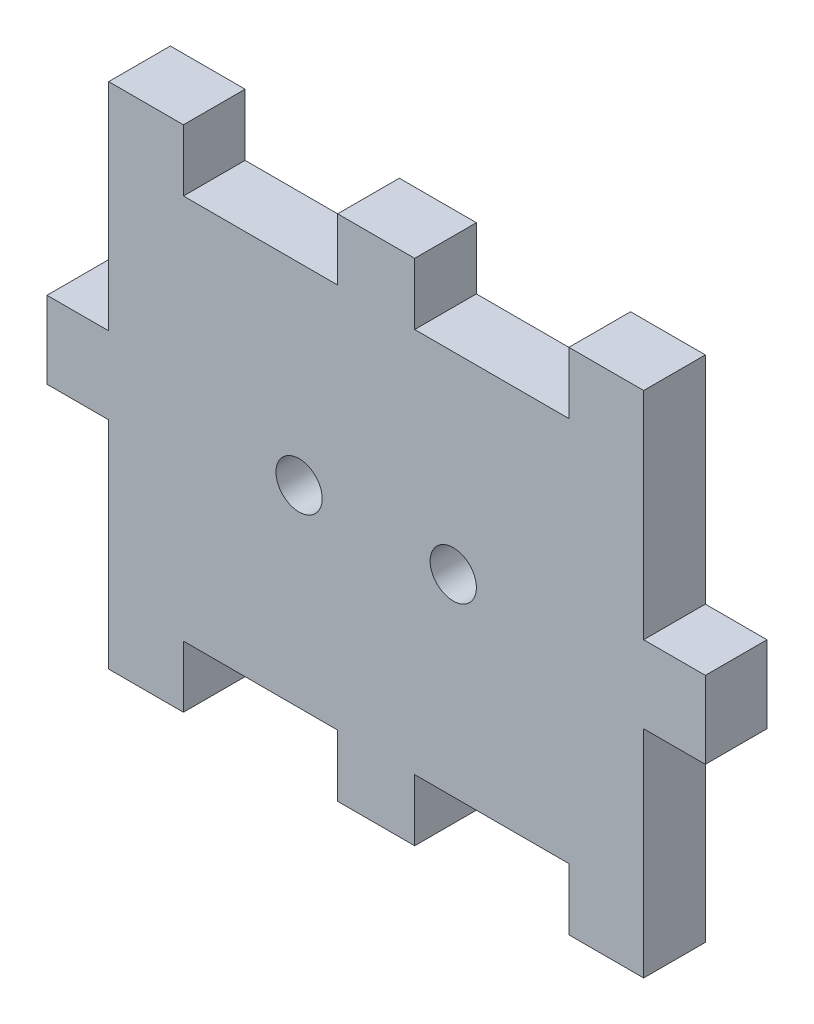
SolidWorks part; units mm, degrees
ref_plane "Спереди" through (0, 0, 0) normal (0, 0, 1) x (1, 0, 0)
ref_plane "Сверху" through (0, 0, 0) normal (0, 1, 0) x (1, 0, 0)
ref_plane "Справа" through (0, 0, 0) normal (1, 0, 0) x (0, 0, -1)
other "Configuration Table"
sketch "Эскиз1" plane through (0, 0, 0) normal (0, 0, 1) x (1, 0, 0)
  line L0 (-4, -4) -> (-4, 29)
  line L1 (0, 0) -> (34.7, 0) construction
  line L2 (0, 0) -> (0, 25) construction
  line L3 (0, 25) -> (34.7, 25) construction
  line L4 (34.7, 0) -> (34.7, 25) construction
  line L7 (-4, 29) -> (38.7, 29)
  line L8 (38.7, -4) -> (38.7, 29)
  line L9 (-4, -4) -> (38.7, -4)
  dimension "D3" = 4
  dimension "D1" = 25
  dimension "D2" = 34.7
extrude "Бобышка-Вытянуть1" add sketch "Эскиз1" along normal blind 4
sketch "Эскиз2" plane through (0, 0, 4) normal (0, 0, 1) x (1, 0, 0)
  line L0 (38.7, 29) -> (-4, 29) construction
  line L1 (4.85, 29) -> (14.85, 29)
  line L2 (4.85, 29) -> (4.85, 25)
  line L3 (4.85, 25) -> (14.85, 25)
  line L4 (14.85, 29) -> (14.85, 25)
  line L5 (17.35, 29) -> (17.35, -4) construction
  line L6 (-4, -4) -> (38.7, -4) construction
  line L7 (19.85, 29) -> (19.85, 25)
  line L8 (29.85, 25) -> (19.85, 25)
  line L9 (29.85, 29) -> (29.85, 25)
  line L10 (29.85, 29) -> (19.85, 29)
  line L11 (-4, 12.5) -> (38.7, 12.5) construction
  line L12 (-4, 29) -> (-4, -4) construction
  line L13 (38.7, -4) -> (38.7, 29) construction
  line L14 (-4, -4) -> (0, -4)
  line L15 (-4, 15) -> (0, 15)
  line L16 (-4, 15) -> (-4, 29)
  line L17 (-4, 29) -> (0, 29)
  line L18 (0, 15) -> (0, 29)
  line L19 (0, 10) -> (0, -4)
  line L20 (-4, 10) -> (0, 10)
  line L21 (-4, 10) -> (-4, -4)
  line L22 (29.85, -4) -> (19.85, -4)
  line L23 (29.85, -4) -> (29.85, 0)
  line L24 (29.85, 0) -> (19.85, 0)
  line L25 (19.85, -4) -> (19.85, 0)
  line L26 (14.85, -4) -> (14.85, 0)
  line L27 (4.85, 0) -> (14.85, 0)
  line L28 (4.85, -4) -> (4.85, 0)
  line L29 (4.85, -4) -> (14.85, -4)
  line L30 (38.7, 10) -> (38.7, -4)
  line L31 (38.7, 10) -> (34.7, 10)
  line L32 (34.7, 10) -> (34.7, -4)
  line L33 (34.7, 15) -> (34.7, 29)
  line L34 (38.7, 29) -> (34.7, 29)
  line L35 (38.7, 15) -> (38.7, 29)
  line L36 (38.7, 15) -> (34.7, 15)
  line L37 (38.7, -4) -> (34.7, -4)
  circle A0 centre (12.35, 12.5) radius 1.5
  circle A1 centre (22.35, 12.5) radius 1.5
  point P48 (12.35, 12.5)
  dimension "D7" = 3
  dimension "D1" = 4
  dimension "D2" = 10
  dimension "D3" = 5
  dimension "D4" = 4
  dimension "D5" = 14
  dimension "D6" = 5
  dimension "D8" = 10
extrude "Вырез-Вытянуть2" cut sketch "Эскиз2" against normal blind 4
